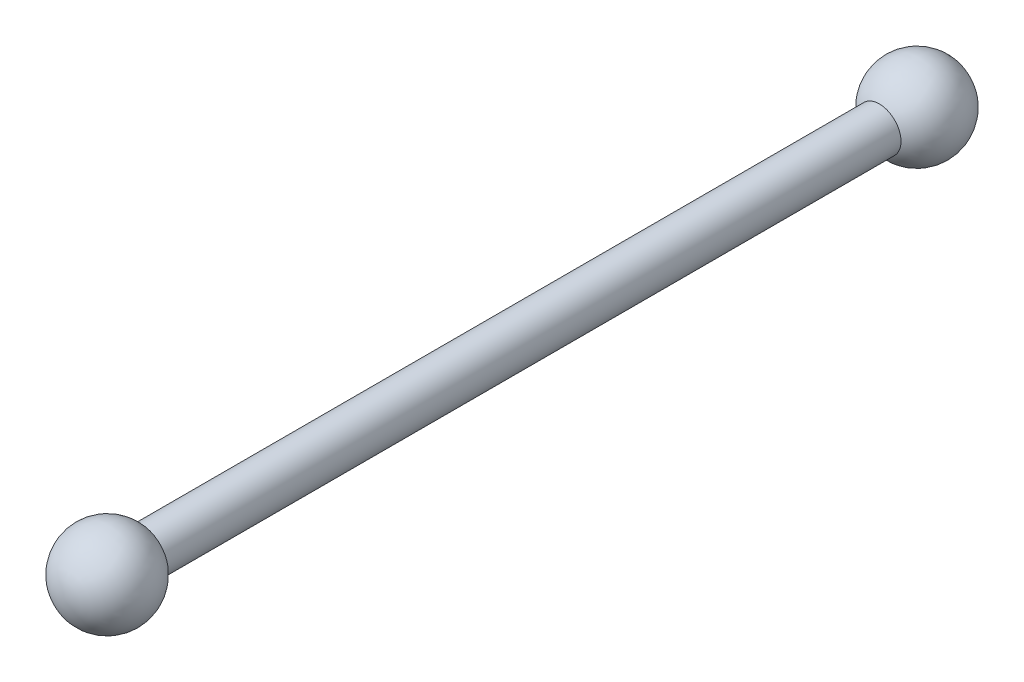
SolidWorks part; units mm, degrees
material "Cast Alloy Steel"
ref_plane "Front Plane" through (0, 0, 0) normal (0, 0, 1) x (1, 0, 0)
ref_plane "Top Plane" through (0, 0, 0) normal (0, 1, 0) x (1, 0, 0)
ref_plane "Right Plane" through (0, 0, 0) normal (1, 0, 0) x (0, 0, -1)
sketch "Sketch1" plane through (0, 0, 0) normal (1, 0, 0) x (0, 0, -1)
  line L0 (13, -0.75) -> (18, -0.75)
  line L1 (-13, 0.75) -> (13, 0.75)
  line L2 (-13, 0.75) -> (-13, -0.75)
  line L3 (-13, -0.75) -> (13, -0.75)
  line L4 (13, 0.75) -> (13, -0.75)
  line L5 (-13, 0.75) -> (13, -0.75) construction
  line L6 (-13, -0.75) -> (13, 0.75) construction
  line L7 (18, -0.75) -> (15, -0.75) construction
  arc A0 (18, -0.75) -> (12.4019, 0.75) centre (15, -0.75) ccw
  point P0 (0, 0)
  dimension "D1" = 1.5
  dimension "D2" = 26
  dimension "D3" = 5
  dimension "D4" = 3
revolve "Revolve1" add sketch "Sketch1" angle 360 about L3
mirror "Mirror1" about plane through (0, 0, 13) normal (0, 0, -1) of "Revolve1"
